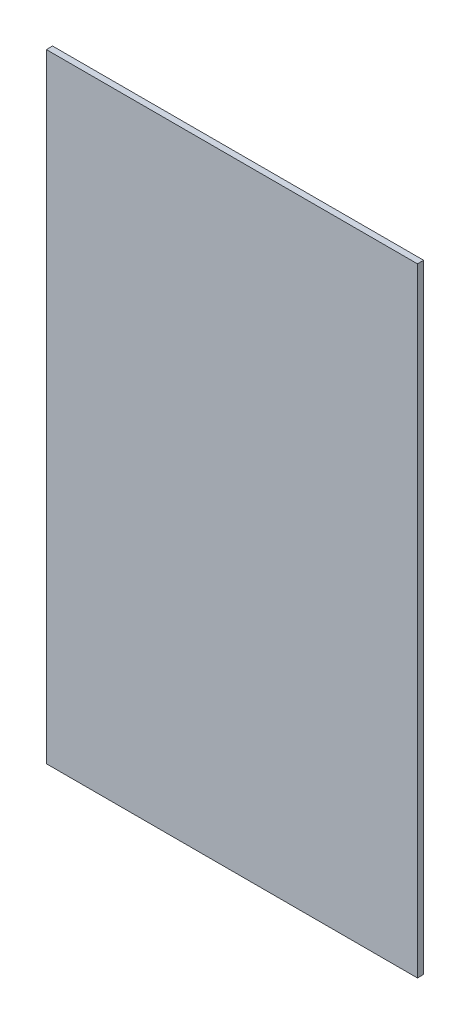
SolidWorks part; units mm, degrees
ref_plane "Front Plane" through (0, 0, 0) normal (0, 0, 1) x (1, 0, 0)
ref_plane "Top Plane" through (0, 0, 0) normal (0, 1, 0) x (1, 0, 0)
ref_plane "Right Plane" through (0, 0, 0) normal (1, 0, 0) x (0, 0, -1)
sketch "Sketch1" plane through (0, 0, 0) normal (0, 0, 1) x (1, 0, 0)
  line L1 (-150, -250) -> (150, -250)
  line L2 (-150, -250) -> (-150, 250)
  line L3 (-150, 250) -> (150, 250)
  line L4 (150, -250) -> (150, 250)
  line L5 (-150, -250) -> (150, 250) construction
  line L6 (-150, 250) -> (150, -250) construction
  point P0 (0, 0)
  dimension "D1" = 300
  dimension "D2" = 500
extrude "Boss-Extrude1" add sketch "Sketch1" along normal blind 5
